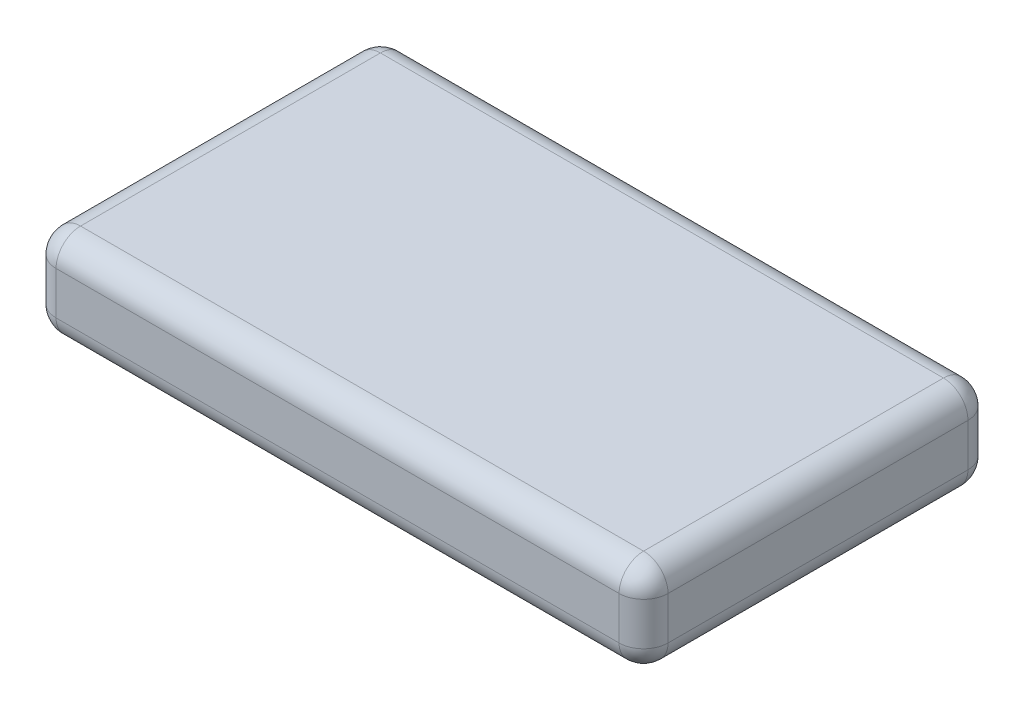
SolidWorks part; units mm, degrees
ref_plane "Front Plane" through (0, 0, 0) normal (0, 0, 1) x (1, 0, 0)
ref_plane "Top Plane" through (0, 0, 0) normal (0, 1, 0) x (1, 0, 0)
ref_plane "Right Plane" through (0, 0, 0) normal (1, 0, 0) x (0, 0, -1)
sketch "Sketch1" plane through (0, 0, 0) normal (0, 1, 0) x (1, 0, 0)
  line L1 (-25, 14.25) -> (25, 14.25)
  line L2 (-25, 14.25) -> (-25, -14.25)
  line L3 (-25, -14.25) -> (25, -14.25)
  line L4 (25, 14.25) -> (25, -14.25)
  line L5 (-25, 14.25) -> (25, -14.25) construction
  line L6 (-25, -14.25) -> (25, 14.25) construction
  point P0 (0, 0)
  dimension "D1" = 28.5
  dimension "D2" = 50
extrude "Boss-Extrude1" add sketch "Sketch1" along normal blind 7.5
fillet "Fillet1" radius 2 12 edges at (25, 3.75, -14.25) (-25, 3.75, -14.25) (0, 0, -14.25) (-25, 0, 0) (25, 0, 0) (-25, 3.75, 14.25) (25, 3.75, 14.25) (0, 0, 14.25) (0, 7.5, 14.25) (-25, 7.5, 0) (0, 7.5, -14.25) (25, 7.5, 0)
